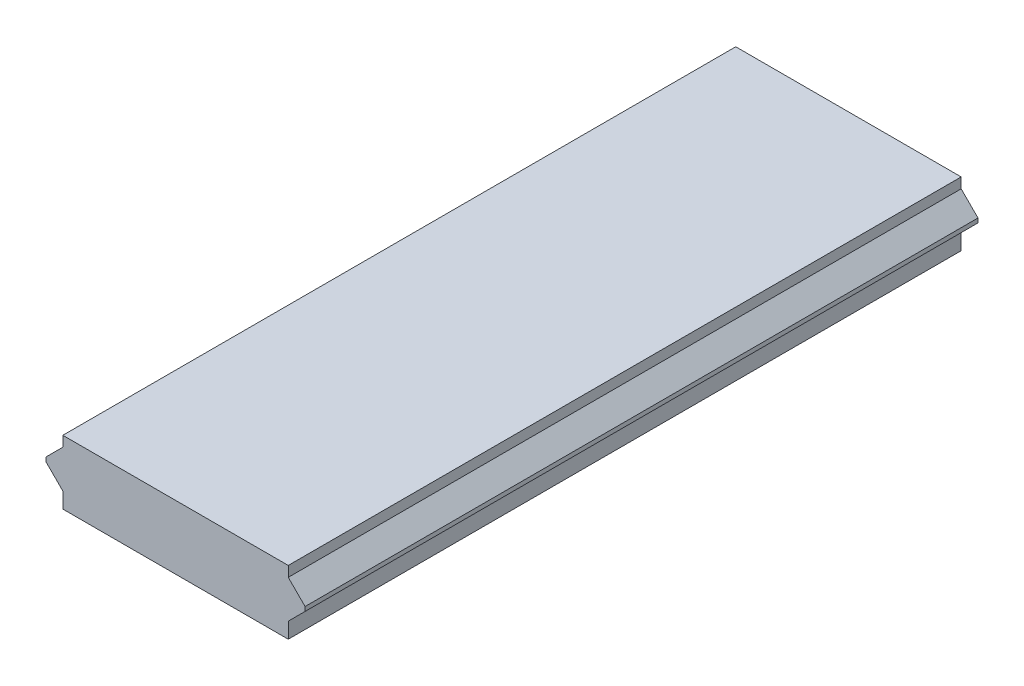
SolidWorks part; units mm, degrees
ref_plane "前视基准面" through (0, 0, 0) normal (0, 0, 1) x (1, 0, 0)
ref_plane "上视基准面" through (0, 0, 0) normal (0, 1, 0) x (1, 0, 0)
ref_plane "右视基准面" through (0, 0, 0) normal (1, 0, 0) x (0, 0, -1)
sketch "草图1" plane through (0, 0, 0) normal (0, 0, 1) x (1, 0, 0)
  line L0 (-39.5, -2.024) -> (-39.5, 44.755) construction
  line L1 (-6, 30.779) -> (-73, 30.779)
  line L2 (-73, 30.779) -> (-73, 35.4359)
  line L3 (-73, 35.4359) -> (-78, 40.4359)
  line L4 (-78, 40.4359) -> (-78, 41.7079)
  line L5 (-78, 41.7079) -> (-73, 46.7079)
  line L6 (-73, 46.7079) -> (-73, 49.779)
  line L7 (-77, 49.779) -> (-74, 49.779) construction
  line L8 (-73, 49.779) -> (-6, 49.779)
  line L9 (-77, 33.779) -> (-83, 39.779) construction
  line L10 (-83, 43.779) -> (-77, 49.779) construction
  line L11 (-74, 3) -> (-74, 28.779) construction
  line L12 (-83, 39.779) -> (-83, 43.779) construction
  line L13 (-6, 46.7079) -> (-6, 49.779)
  line L14 (-1, 41.7079) -> (-6, 46.7079)
  line L15 (-1, 40.4359) -> (-1, 41.7079)
  line L16 (-6, 35.4359) -> (-1, 40.4359)
  line L17 (-6, 30.779) -> (-6, 35.4359)
  point P1 (-78, 41.0719)
  point P21 (-39.5, 49.779)
  point P26 (-39.5, 30.779)
  dimension "D1" = 1
  dimension "D2" = 4
  dimension "D3" = 5
  dimension "D4" = 5
  dimension "D5" = 19
  dimension "D6" = 77
extrude "凸台-拉伸1" add sketch "草图1" against normal blind 200
